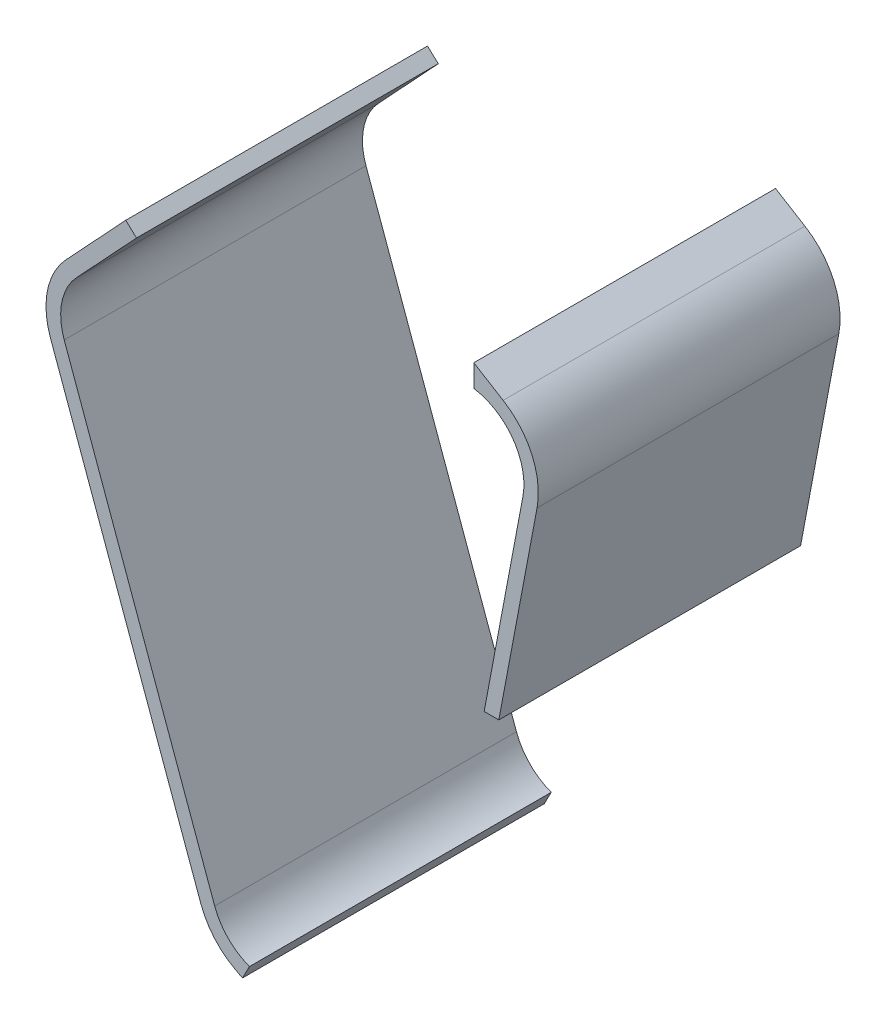
SolidWorks part; units mm, degrees
ref_plane "前视基准面" through (0, 0, 0) normal (0, 0, 1) x (1, 0, 0)
ref_plane "上视基准面" through (0, 0, 0) normal (0, 1, 0) x (1, 0, 0)
ref_plane "右视基准面" through (0, 0, 0) normal (1, 0, 0) x (0, 0, -1)
other "Configuration Table"
sketch "草图1" plane through (0, 0, 0) normal (0, 0, 1) x (1, 0, 0)
  line L1 (-192.5971, -21.2394) -> (-295.1186, 261.4588) construction
  line L2 (-286.7701, 302.3748) -> (-245.8518, 346.2574) construction
  line L6 (-8.9955, 185.3267) -> (1.0045, 185.3267)
  line L7 (-173.6383, -54.2647) -> (-168.8775, -45.1155)
  line L11 (-192.5971, -21.2394) -> (-295.1186, 261.4588)
  line L12 (-286.7701, 302.3748) -> (-245.8518, 346.2574)
  line L13 (-245.8518, 346.2574) -> (-253.1656, 353.0772)
  line L15 (-8.9955, 185.3267) -> (17.3868, 325.2271)
  line L33 (0.866, 184.5924) -> (27.0434, 323.406)
  line L34 (3.9398, 375.3615) -> (-17.8515, 388.6489)
  line L37 (-8.9955, 185.3267) -> (17.3868, 325.2271) construction
  line L40 (-8.9955, 185.3267) -> (0.866, 185.3267) construction
  line L41 (-253.1656, 353.0772) -> (-245.8518, 346.2574) construction
  line L44 (-42.4768, 395.9394) -> (-186.2642, 399.9818)
  line L46 (-224.2383, 384.1001) -> (-294.0839, 309.1945)
  line L47 (-304.5195, 258.0495) -> (-201.998, -24.6487)
  line L49 (-178.0738, -51.9566) -> (-107.7247, -88.5635)
  line L58 (-55.6445, -84.9401) -> (-21, -60.2736)
  line L59 (0, -19.5427) -> (0, 175.3267)
  line L60 (1.0045, 185.3267) -> (27.0434, 323.406)
  line L61 (3.9398, 375.3615) -> (-16.0602, 387.5566)
  line L64 (-253.1656, 353.0772) -> (-294.0839, 309.1945)
  line L67 (-304.5195, 258.0495) -> (-201.998, -24.6487)
  line L68 (-178.0738, -51.9566) -> (-173.6383, -54.2647)
  line L101 (-16.0602, 372.3897) -> (-16.0602, 387.5566)
  arc A0 (-192.5971, -21.2394) -> (-168.8775, -45.1155) centre (-154.9935, -7.6023) ccw
  arc A9 (-286.7701, 302.3748) -> (-295.1186, 261.4588) centre (-257.515, 275.0959) ccw
  arc A10 (17.3868, 325.2271) -> (-16.0602, 372.3897) centre (-22.0906, 332.6717) ccw
  arc A11 (27.0434, 323.406) -> (3.9398, 375.3615) centre (-22.0906, 332.6717) ccw
  arc A12 (-17.8515, 388.6489) -> (-42.4768, 395.9394) centre (-43.8819, 345.9591) ccw
  arc A15 (-186.2642, 399.9818) -> (-224.2383, 384.1001) centre (-187.6694, 350.0015) ccw
  arc A16 (-294.0839, 309.1945) -> (-304.5195, 258.0495) centre (-257.515, 275.0959) ccw
  arc A19 (-201.998, -24.6487) -> (-178.0738, -51.9566) centre (-154.9935, -7.6023) ccw
  arc A21 (-107.7247, -88.5635) -> (-55.6445, -84.9401) centre (-84.6445, -44.2092) ccw
  arc A24 (-21, -60.2736) -> (0, -19.5427) centre (-50, -19.5427) ccw
  arc A25 (0.866, 184.5924) -> (0, 175.3267) centre (50, 175.3267) ccw
  arc A26 (27.0434, 323.406) -> (3.9398, 375.3615) centre (-22.0906, 332.6717) ccw
  arc A31 (-294.0839, 309.1945) -> (-304.5195, 258.0495) centre (-257.515, 275.0959) ccw
  arc A35 (-201.998, -24.6487) -> (-178.0738, -51.9566) centre (-154.9935, -7.6023) ccw
  dimension "D2" = 9.8268
  dimension "D3" = 10
  dimension "D4" = 10
  dimension "D5" = 60
  dimension "D1" = 0
  dimension "D6" = 5
  dimension "D7" = 20
  dimension "D8" = 10
extrude "凸台-拉伸1" add sketch "草图1" along normal blind 205.6
